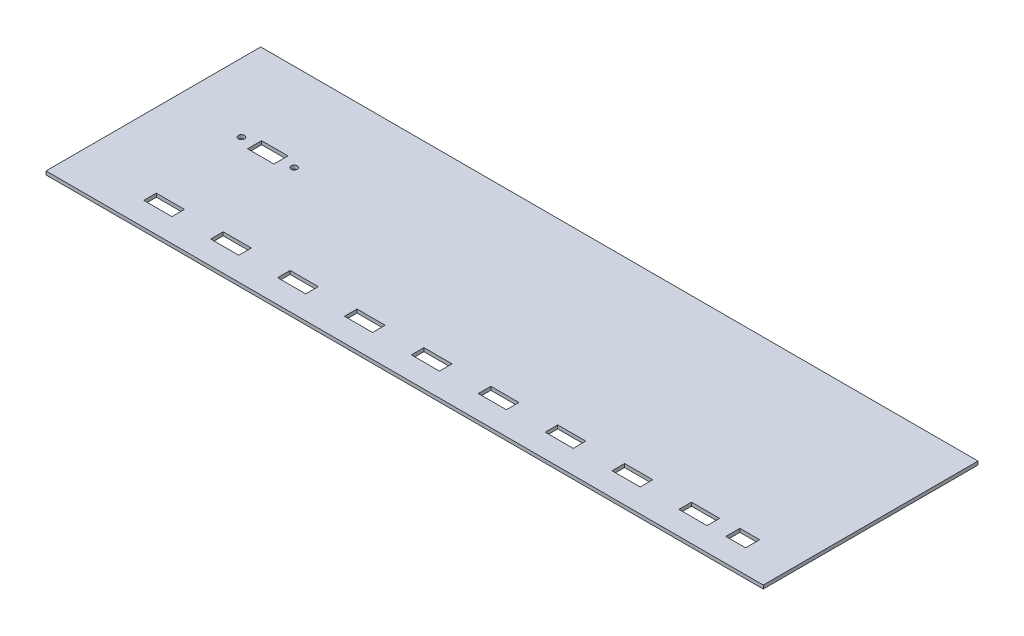
SolidWorks part; units mm, degrees
ref_plane "Front Plane" through (0, 0, 0) normal (0, 0, 1) x (1, 0, 0)
ref_plane "Top Plane" through (0, 0, 0) normal (0, 1, 0) x (1, 0, 0)
ref_plane "Right Plane" through (0, 0, 0) normal (1, 0, 0) x (0, 0, -1)
sketch "Sketch1" plane through (0, 0, 0) normal (0, 1, 0) x (1, 0, 0)
  line L0 (309.09, 20.45) -> (325.09, 20.45)
  line L1 (0, 0) -> (408.5, 0)
  line L2 (0, 0) -> (0, 122.3)
  line L3 (0, 122.3) -> (408.5, 122.3)
  line L4 (408.5, 0) -> (408.5, 122.3)
  line L5 (373.875, 21.3) -> (385.125, 21.3)
  line L6 (373.875, 21.3) -> (373.875, 13.3)
  line L7 (373.875, 13.3) -> (385.125, 13.3)
  line L8 (385.125, 21.3) -> (385.125, 13.3)
  line L9 (347.19, 20.45) -> (363.19, 20.45)
  line L10 (347.19, 20.45) -> (347.19, 13.3)
  line L11 (347.19, 13.3) -> (363.19, 13.3)
  line L12 (363.19, 20.45) -> (363.19, 13.3)
  line L13 (309.09, 20.45) -> (309.09, 13.3)
  line L14 (325.09, 20.45) -> (325.09, 13.3)
  line L15 (309.09, 13.3) -> (325.09, 13.3)
  line L16 (270.99, 20.45) -> (286.99, 20.45)
  line L17 (270.99, 20.45) -> (270.99, 13.3)
  line L18 (286.99, 20.45) -> (286.99, 13.3)
  line L19 (270.99, 13.3) -> (286.99, 13.3)
  line L20 (232.89, 20.45) -> (248.89, 20.45)
  line L21 (232.89, 20.45) -> (232.89, 13.3)
  line L22 (248.89, 20.45) -> (248.89, 13.3)
  line L23 (232.89, 13.3) -> (248.89, 13.3)
  line L24 (194.79, 20.45) -> (210.79, 20.45)
  line L25 (194.79, 20.45) -> (194.79, 13.3)
  line L26 (210.79, 20.45) -> (210.79, 13.3)
  line L27 (194.79, 13.3) -> (210.79, 13.3)
  line L28 (156.69, 20.45) -> (172.69, 20.45)
  line L29 (156.69, 20.45) -> (156.69, 13.3)
  line L30 (172.69, 20.45) -> (172.69, 13.3)
  line L31 (156.69, 13.3) -> (172.69, 13.3)
  line L32 (118.59, 20.45) -> (134.59, 20.45)
  line L33 (118.59, 20.45) -> (118.59, 13.3)
  line L34 (134.59, 20.45) -> (134.59, 13.3)
  line L35 (118.59, 13.3) -> (134.59, 13.3)
  line L36 (80.49, 20.45) -> (96.49, 20.45)
  line L37 (80.49, 20.45) -> (80.49, 13.3)
  line L38 (96.49, 20.45) -> (96.49, 13.3)
  line L39 (80.49, 13.3) -> (96.49, 13.3)
  line L40 (42.39, 20.45) -> (58.39, 20.45)
  line L41 (42.39, 20.45) -> (42.39, 13.3)
  line L42 (58.39, 20.45) -> (58.39, 13.3)
  line L43 (42.39, 13.3) -> (58.39, 13.3)
  line L45 (46.5, 76.3) -> (61.5, 76.3)
  line L46 (46.5, 76.3) -> (46.5, 68.3)
  line L47 (46.5, 68.3) -> (61.5, 68.3)
  line L48 (61.5, 76.3) -> (61.5, 68.3)
  circle A0 centre (39, 72.3) radius 1.75
  circle A1 centre (69, 72.3) radius 1.75
  point P54 (61.5, 72.3)
  dimension "D12" = 3.5
  dimension "D1" = 408.5
  dimension "D2" = 122.3
  dimension "D3" = 11.25
  dimension "D4" = 34.625
  dimension "D5" = 8
  dimension "D6" = 13.3
  dimension "D7" = 16
  dimension "D8" = 7.15
  dimension "D9" = 45.31
  dimension "D11" = 38.1
  dimension "D13" = 30
  dimension "D14" = 15
  dimension "D15" = 7.5
  dimension "D16" = 8
  dimension "D17" = 39
  dimension "D18" = 50
  dimension "D10" = 9
extrude "Boss-Extrude1" add sketch "Sketch1" along normal blind 2
equation "\"D15@Sketch1\"=(\"D13@Sketch1\"-\"D14@Sketch1\")/2"
